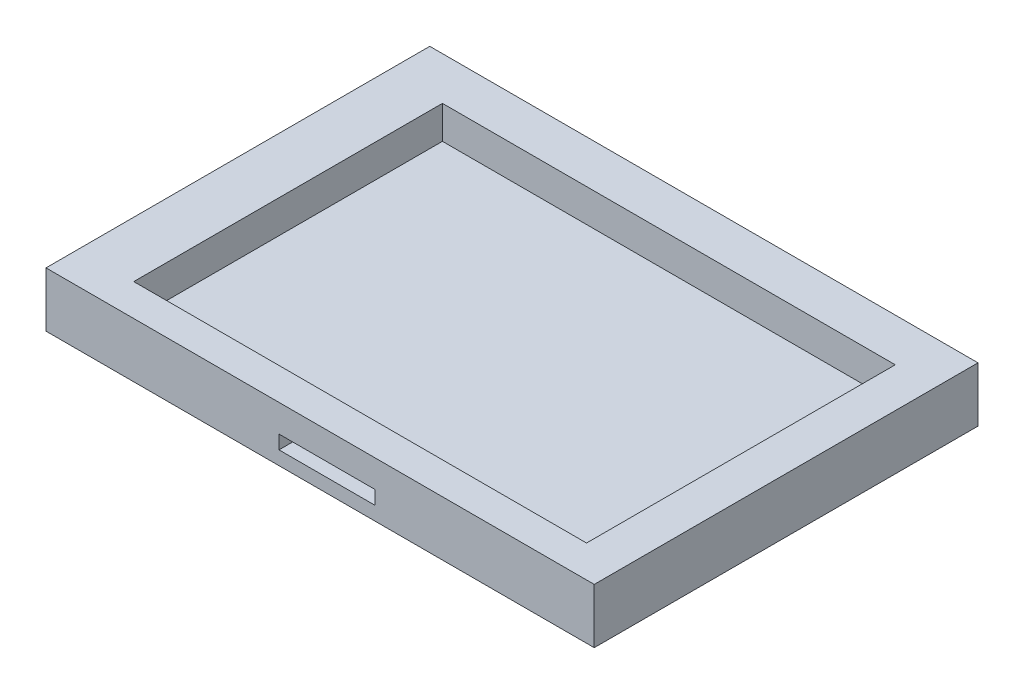
SolidWorks part; units mm, degrees
ref_plane "Front Plane" through (0, 0, 0) normal (0, 0, 1) x (1, 0, 0)
ref_plane "Top Plane" through (0, 0, 0) normal (0, 1, 0) x (1, 0, 0)
ref_plane "Right Plane" through (0, 0, 0) normal (1, 0, 0) x (0, 0, -1)
sketch "Sketch1" plane through (0, 0, 0) normal (0, 1, 0) x (1, 0, 0)
  line L1 (-250, 175) -> (250, 175)
  line L2 (-250, 175) -> (-250, -175)
  line L3 (-250, -175) -> (250, -175)
  line L4 (250, 175) -> (250, -175)
  line L5 (-250, 175) -> (250, -175) construction
  line L6 (-250, -175) -> (250, 175) construction
  point P0 (0, 0)
  dimension "D1" = 350
  dimension "D2" = 500
extrude "Boss-Extrude1" add sketch "Sketch1" along normal blind 20
sketch "Sketch2" plane through (0, 20, 0) normal (0, 1, 0) x (1, 0, 0)
  line L0 (-250, -175) -> (250, -175) construction
  line L1 (-250, 175) -> (-199.1585, 175)
  line L2 (-250, 175) -> (-250, -175)
  line L3 (-250, -175) -> (-199.1585, -175)
  line L4 (-199.1585, 135.721) -> (-199.1585, -145.8306)
  line L5 (250, 175) -> (-250, 175) construction
  line L6 (-199.1585, 135.721) -> (213.8174, 135.721)
  line L8 (-199.1585, 175) -> (250, 175)
  line L9 (250, 135.721) -> (250, 175)
  line L12 (213.8174, 135.721) -> (213.8174, -145.8306)
  line L13 (213.8174, -175) -> (250, -175)
  line L14 (250, 135.721) -> (250, -175)
  line L15 (-199.1585, -145.8306) -> (213.8174, -145.8306)
  line L17 (-199.1585, -175) -> (213.8174, -175)
extrude "Boss-Extrude2" add sketch "Sketch2" along normal blind 30
sketch "Sketch3" plane through (0, 0, 175) normal (0, 0, 1) x (1, 0, 0)
  line L0 (-250, 0) -> (250, 0) construction
  line L1 (-37.5, 25) -> (50, 25)
  line L2 (-37.5, 25) -> (-37.5, 12.5)
  line L3 (-37.5, 12.5) -> (50, 12.5)
  line L4 (50, 25) -> (50, 12.5)
  line L5 (250, 50) -> (250, 0) construction
  dimension "D1" = 87.5
  dimension "D2" = 12.5
  dimension "D3" = 25
  dimension "D4" = 200
extrude "Cut-Extrude2" cut sketch "Sketch3" against normal blind 20
